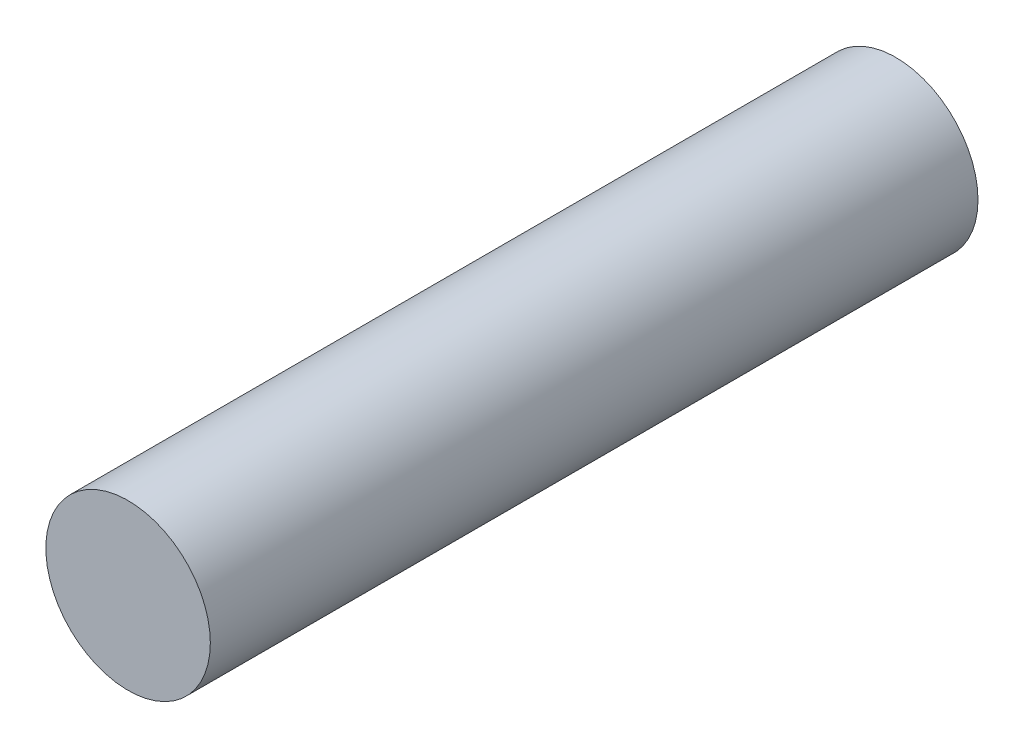
SolidWorks part; units mm, degrees
ref_plane "Plan de face" through (0, 0, 0) normal (0, 0, 1) x (1, 0, 0)
ref_plane "Plan de dessus" through (0, 0, 0) normal (0, 1, 0) x (1, 0, 0)
ref_plane "Plan de droite" through (0, 0, 0) normal (1, 0, 0) x (0, 0, -1)
sketch "Esquisse1" plane through (0, 0, 0) normal (0, 0, 1) x (1, 0, 0)
  circle A0 centre (0, 0) radius 7.5
  dimension "D1" = 15
extrude "Boss.-Extru.1" add sketch "Esquisse1" along normal blind 70
